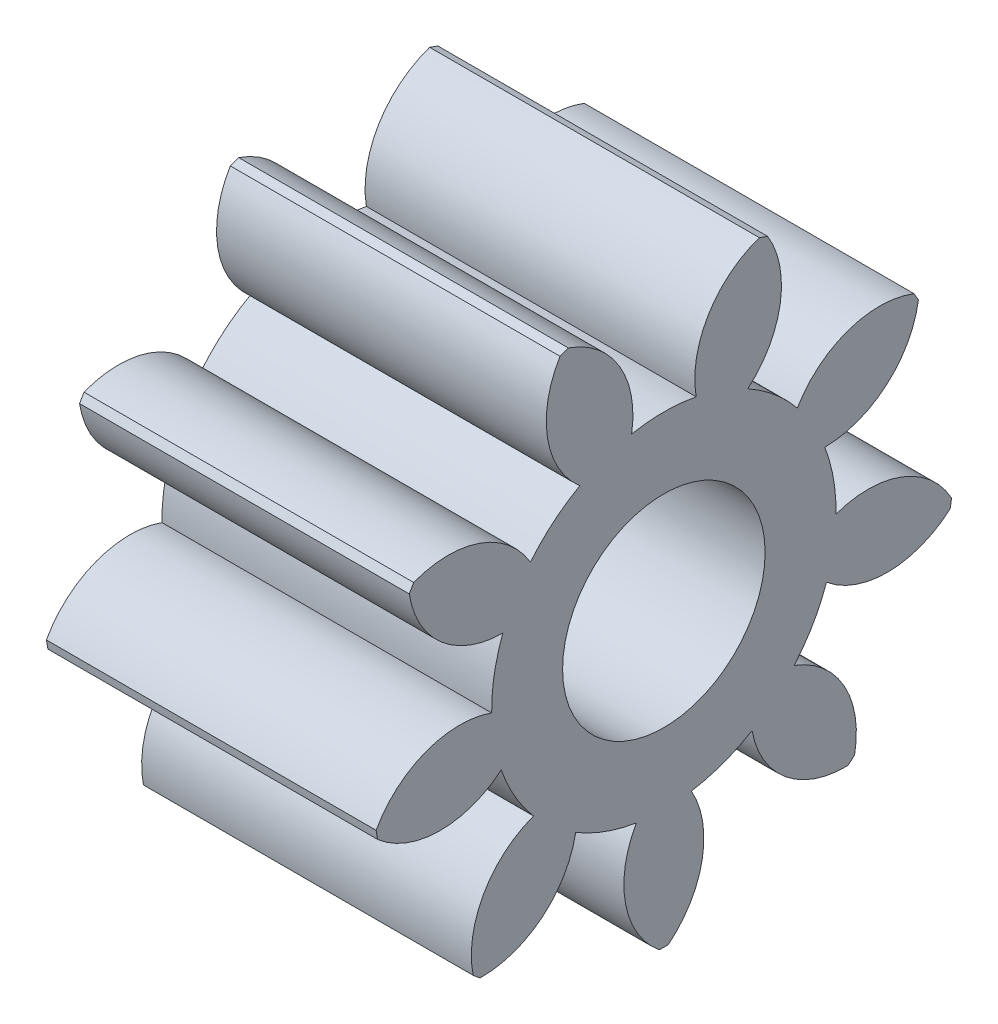
SolidWorks part; units mm, degrees
ref_plane "Plane1" through (0, 0, 0) normal (0, 0, 1) x (1, 0, 0)
ref_plane "Plane2" through (0, 0, 0) normal (0, 1, 0) x (1, 0, 0)
ref_plane "Plane3" through (0, 0, 0) normal (1, 0, 0) x (0, 0, -1)
sketch "HoldingSke" plane through (0, 0, 0) normal (0, 1, 0) x (1, 0, 0)
  line L0 (0, 0) -> (0.439, -0.0695)
  line L1 (-15, 0) -> (100, 0) construction
  line L2 (0, 0) -> (-2.1039, 2.3779)
  line L3 (0, 0) -> (-11.863, 4.5341)
  line L4 (0, 0) -> (8.5297, 1.351)
  line L5 (0, 0) -> (-46.8476, -17.4728)
  line L6 (0, 0) -> (-11.6055, -7.8303)
  line L7 (-2.1039, 2.3779) -> (8.6586, 51.2059)
  line L8 (-76.2, 54.61) -> (-74.8, 54.61)
  line L9 (-71.009, 38.7566) -> (-53.1078, 45.2721)
  line L10 (-76.2, 71.12) -> (104.1128, 71.12)
  line L11 (0, 0) -> (-14, 0)
  line L12 (-76.2, 101.6) -> (-76.123, 101.6)
  line L13 (24.9733, 27.94) -> (52.9518, 28.4284)
  line L14 (24.9733, 27.94) -> (24.9743, 27.94)
  line L15 (24.9733, 27.94) -> (100.4006, 29.5858)
  line L16 (-63.627, -2.25) -> (-12.827, -2.25)
  circle A0 centre (0, 0) radius 4
  circle A1 centre (0, 0) radius 7.3115
  circle A2 centre (0, 0) radius 37.5
  circle A3 centre (0, 0) radius 4
  dimension "MHD" = 14.623
  dimension "Hub_dia" = 75
  dimension "Bore" = 8
  dimension "MBD" = 8
  dimension "Num_teeth" = 9
  dimension "Pitch" = 0.4444
  dimension "Overall_len" = 50
  dimension "Show_teeth" = 9
  dimension "Thickness" = 14
  dimension "OAL" = 50.0001
  dimension "T_dim" = 1.4
  dimension "Ap" = 20
  dimension "H" = 19.05
  dimension "Pitch_radius" = 180.3128
  dimension "Width" = 14
  dimension "Backlash" = 0.077
  dimension "Addendum_fac" = 1
  dimension "Dedendum_fac" = 1.25
  dimension "Clearance_fac" = 0.25
  dimension "Dedendum_add" = 0.001
  dimension "Module" = 2.25
sketch "BasProSke" plane through (0, 0, 0) normal (0, 1, 0) x (1, 0, 0)
  line L0 (-10, 0) -> (60, 0) construction
  line L1 (0, 0) -> (0, 12.375)
  line L2 (0, 0) -> (14, 0)
  line L3 (14, 0) -> (14, 12.375)
  line L4 (14, 12.375) -> (0, 12.375)
  dimension "Thickness" = 14
  dimension "Diameter" = 24.75
revolve "Base-Revolve" add sketch "BasProSke" angle 360 about L0
sketch "TooCutSke" plane through (0, 0, 0) normal (1, 0, 0) x (0, 0, -1)
  line L1 (0, 0) -> (0, 107) construction
  line L2 (0, 0) -> (-1.8926, 9.9465) construction
  line L3 (0, 0) -> (-6.8363, 18.7826) construction
  line L4 (-1.8926, 9.9465) -> (-3.4181, 9.3913) construction
  arc A0 (1.37, 7.182) -> (-1.37, 7.182) centre (0, 0) ccw
  arc A1 (4.0943, 11.705) -> (-4.0943, 11.705) centre (0, 0) ccw
  circle A2 centre (0, 0) radius 10.125 construction
  circle A3 centre (0, 0) radius 9.5144 construction
  arc A4 (-1.37, 7.182) -> (-4.0943, 11.705) centre (-5.3631, 7.8588) ccw
  arc A5 (4.0943, 11.705) -> (1.37, 7.182) centre (5.3631, 7.8588) ccw
  dimension "Root_dia" = 14.623
  dimension "Overcut_dia" = 24.8008
  dimension "Pitch_dia" = 20.25
  dimension "Base_dia" = 19.0288
  dimension "Flank_rad" = 4.05
  dimension "Half_ang" = 20
  dimension "Half_CT" = 1.6234
extrude "ToothCut" cut sketch "TooCutSke" along normal through all
fillet "Breaks" [suppressed] radius 0.045
fillet "RootFillets" [suppressed] radius 0.5635
pattern_circular "TeethCuts" count 9 every 40 about axis through (-10, 0, 0) along (1, 0, 0) of "ToothCut", "RootFillets", "Breaks"
sketch "HubNeaOneSke" plane through (0, 0, 0) normal (-1, 0, 0) x (0, 0, 1)
  circle A0 centre (0, 0) radius 7.3115
  dimension "Diameter" = 14.623
extrude "HubNearOne" [suppressed] add sketch "HubNeaOneSke" along normal blind 36.0001
sketch "HubNeaBotSke" plane through (0, 0, 0) normal (-1, 0, 0) x (0, 0, 1)
  circle A0 centre (0, 0) radius 7.3115
  dimension "Diameter" = 14.623
extrude "HubNearBoth" [suppressed] add sketch "HubNeaBotSke" along normal blind 18
ref_plane "FarPln" through (14, 0, 0) normal (1, 0, 0) x (0, 0, -1)
sketch "HubFarSke" plane through (14, 0, 0) normal (1, 0, 0) x (0, 0, -1)
  circle A0 centre (0, 0) radius 7.3115
  dimension "Diameter" = 14.623
extrude "HubFar" [suppressed] add sketch "HubFarSke" along normal blind 18
sketch "BorSke" plane through (0, 0, 0) normal (1, 0, 0) x (0, 0, -1)
  circle A0 centre (0, 0) radius 4
  dimension "Diameter" = 8
extrude "Bore" cut sketch "BorSke" along normal mid plane 100.0001
sketch "KeySke" plane through (0, 0, 0) normal (1, 0, 0) x (0, 0, -1)
  line L0 (-1.5, 0) -> (-1.5, 5.4)
  line L1 (-1.5, 5.4) -> (1.5, 5.4)
  line L2 (1.5, 5.4) -> (1.5, 0)
  line L3 (0, 0) -> (0, 34) construction
  line L4 (-1.5, 0) -> (1.5, 0)
  dimension "Offset" = 5.4
  dimension "Width" = 3
extrude "Keyway" [suppressed] cut sketch "KeySke" along normal mid plane 100.0001
pattern_circular "Keyway2" [suppressed] count 2 every 90 about axis through (-10, 0, 0) along (1, 0, 0)
sketch "Sketch1" plane through (14, 0, 0) normal (1, 0, 0) x (0, 0, -1)
  circle A0 centre (0, 0) radius 4.3
extrude "Cut-Extrude1" cut sketch "Sketch1" against normal through all
equation "' \"Module@HoldingSke\" = 6.35"
equation "' \"Num_teeth@HoldingSke\" = 12"
equation "' \"Ap@HoldingSke\" =  20"
equation "' \"Ap@HoldingSke\" = 20"
equation "' \"Width@HoldingSke\" = 0.5 * 25.4"
equation "' \"Hub_dia@HoldingSke\"= 1 * 25.4"
equation "' \"Hub_dia@HoldingSke\" = 1 * 25.4"
equation "' \"Overall_len@HoldingSke\" = 1.0 * 25.4"
equation "' \"Bore@HoldingSke\" = 0.75 * 25.4"
equation "' \"T_dim@HoldingSke\" = 0.1 * 25.4"
equation "' \"Width@KeySke\" = 0.25 * 25.4"
equation "' \"Show_teeth@HoldingSke\" = 13"
equation "' \"Backlash@HoldingSke\" = 0.009 * 25.4"
equation "' \"Addendum_fac@HoldingSke\" = 1.0"
equation "' \"Dedendum_fac@HoldingSke\" = 1.25"
equation "' \"Dedendum_add@HoldingSke\" = 0.00005 * 25.4"
equation "' \"Clearance_fac@HoldingSke\" = 0.25"
equation "\"Pitch@HoldingSke\" = 1 / \"Module@HoldingSke\""
equation "\"Overcut_dia@TooCutSke\" = (\"Num_teeth@HoldingSke\" + 2 * \"Addendum_fac@HoldingSke\") / \"Pitch@HoldingSke\" + 0.002 * 25.4"
equation "\"Pitch_dia@TooCutSke\" = \"Num_teeth@HoldingSke\" / \"Pitch@HoldingSke\""
equation "\"Base_dia@TooCutSke\" = \"Num_teeth@HoldingSke\" / \"Pitch@HoldingSke\" * cos((\"Ap@HoldingSke\"  * 3.14159265 / 180))"
equation "\"Root_dia@TooCutSke\" = (\"Num_teeth@HoldingSke\" + 2) / \"Pitch@HoldingSke\" - 2 * (\"Addendum_fac@HoldingSke\" + \"Dedendum_fac@HoldingSke\") / \"Pitch@HoldingSke\" - \"Dedendum_add@HoldingSke\" * 2"
equation "\"Half_ang@TooCutSke\" = 180 / \"Num_teeth@HoldingSke\""
equation "\"Half_CT@TooCutSke\" = \"Num_teeth@HoldingSke\" / \"Pitch@HoldingSke\" * sin((3.14159265 / 2 / \"Num_teeth@HoldingSke\")) / 2 - 7 * \"Backlash@HoldingSke\" / 4"
equation "\"Flank_rad@TooCutSke\" = \"Num_teeth@HoldingSke\" / \"Pitch@HoldingSke\" / 5"
equation "\"Radius@RootFillets\" = \"Clearance_fac@HoldingSke\" / \"Pitch@HoldingSke\" + \"Dedendum_add@HoldingSke\""
equation "\"Break_rad@Breaks\" = 0.02 / \"Pitch@HoldingSke\""
equation "\"Thickness@HoldingSke\" = \"Width@HoldingSke\""
equation "\"OAL@HoldingSke\" = \"Thickness@HoldingSke\""
equation "\"MHD@HoldingSke\" = (\"Num_teeth@HoldingSke\" + 2) / \"Pitch@HoldingSke\" - 2 * (\"Addendum_fac@HoldingSke\" + \"Dedendum_fac@HoldingSke\")  / \"Pitch@HoldingSke\" - \"Dedendum_add@HoldingSke\" * 2"
equation "\"MBD@HoldingSke\" = (\"Num_teeth@HoldingSke\" + 2) / \"Pitch@HoldingSke\" - 2 * (\"Addendum_fac@HoldingSke\" + \"Dedendum_fac@HoldingSke\")  / \"Pitch@HoldingSke\" - \"Dedendum_add@HoldingSke\" * 2 - 0.002 * 25.4"
equation "\"MHD@HoldingSke\" = ((sgn( \"MHD@HoldingSke\" - \"Hub_dia@HoldingSke\" )-1)*( \"MHD@HoldingSke\" - \"Hub_dia@HoldingSke\" ))/-2+ \"Hub_dia@HoldingSke\""
equation "\"MBD@HoldingSke\" = ((sgn( \"MBD@HoldingSke\" - \"Bore@HoldingSke\" )-1)*( \"MBD@HoldingSke\" - \"Bore@HoldingSke\" ))/-2+ \"Bore@HoldingSke\""
equation "\"OAL@HoldingSke\" = ((sgn( \"OAL@HoldingSke\" - \"Overall_len@HoldingSke\" )+1)*( \"OAL@HoldingSke\" - \"Overall_len@HoldingSke\" ))/2 + \"Overall_len@HoldingSke\" + 0.000002 * 25.4"
equation "\"Num_teeth@TeethCuts\" = int( \"Show_teeth@HoldingSke\" ) + 1"
equation "\"Num_teeth@TeethCuts\" = ((sgn( \"Num_teeth@TeethCuts\" - \"Num_teeth@HoldingSke\" )-1)*( \"Num_teeth@TeethCuts\" - \"Num_teeth@HoldingSke\" ))/-2+ \"Num_teeth@HoldingSke\""
equation "\"Num_teeth@TeethCuts\" = ((sgn( \"Num_teeth@TeethCuts\" - 2.0)+1)*( \"Num_teeth@TeethCuts\" - 2.0))/2 +2.0"
equation "\"Angle@TeethCuts\" = 360.0 / \"Num_teeth@HoldingSke\""
equation "\"Diameter@BasProSke\" = (\"Num_teeth@HoldingSke\" + 2 * \"Addendum_fac@HoldingSke\") / \"Pitch@HoldingSke\""
equation "\"Thickness@BasProSke\"  = \"Thickness@HoldingSke\""
equation "' \"Fillet_rad@BasProSke\" =  \"Thickness@HoldingSke\" * 0.05"
equation "' \"Fillet_rad@BasProSke\" = \"Thickness@HoldingSke\" * 0.05"
equation "\"MHD@HoldingSke\" = ((sgn( \"MHD@HoldingSke\" - \"Root_dia@TooCutSke\" )-1)*( \"MHD@HoldingSke\" - \"Root_dia@TooCutSke\" ))/-2+ \"Root_dia@TooCutSke\""
equation "\"Diameter@HubNeaOneSke\" = \"MHD@HoldingSke\""
equation "\"Length@HubNearOne\" = \"OAL@HoldingSke\" - \"Thickness@BasProSke\""
equation "\"Diameter@HubNeaBotSke\" = \"MHD@HoldingSke\""
equation "\"Length@HubNearBoth\" = ( \"OAL@HoldingSke\" - \"Thickness@BasProSke\" ) / 2.0"
equation "\"Thickness@FarPln\" = \"Thickness@BasProSke\""
equation "\"Diameter@HubFarSke\" = \"MHD@HoldingSke\""
equation "\"Length@HubFar\" = ( \"OAL@HoldingSke\" - \"Thickness@BasProSke\" ) / 2.0"
equation "\"Diameter@BorSke\" = \"MBD@HoldingSke\""
equation "\"D1@Bore\" = \"OAL@HoldingSke\" * 2.0"
equation "\"D1@Keyway\" = \"OAL@HoldingSke\" * 2.0"
equation "\"Offset@KeySke\" = \"T_dim@HoldingSke\" + \"MBD@HoldingSke\" / 2.0"
